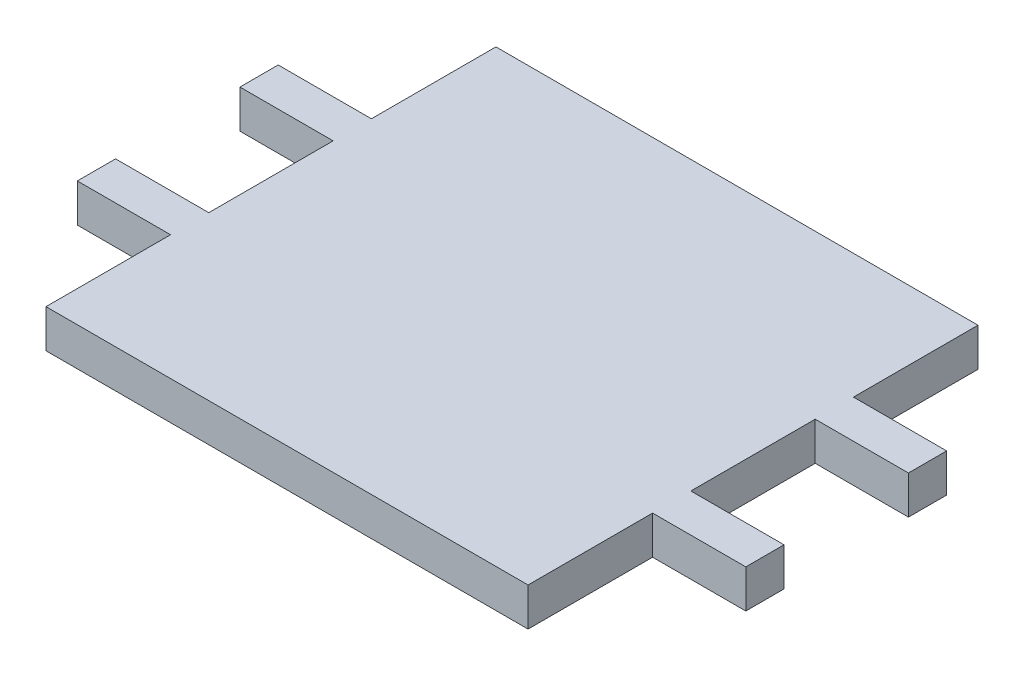
SolidWorks part; units mm, degrees
ref_plane "Front Plane" through (0, 0, 0) normal (0, 0, 1) x (1, 0, 0)
ref_plane "Top Plane" through (0, 0, 0) normal (0, 1, 0) x (1, 0, 0)
ref_plane "Right Plane" through (0, 0, 0) normal (1, 0, 0) x (0, 0, -1)
sketch "Sketch1" plane through (0, 0, 0) normal (0, 1, 0) x (1, 0, 0)
  line L0 (0, 35.56) -> (0, -35.56) construction
  line L1 (-38.1, 35.56) -> (38.1, 35.56)
  line L2 (-38.1, 35.56) -> (-38.1, -35.56)
  line L3 (-38.1, -35.56) -> (38.1, -35.56)
  line L4 (38.1, 35.56) -> (38.1, -35.56)
  line L5 (-38.1, 0) -> (38.1, 0) construction
  line L6 (-52.832, 9.8298) -> (-52.832, -9.8298) construction
  line L7 (-52.832, 15.875) -> (-38.1, 15.875)
  line L8 (-52.832, 15.875) -> (-52.832, 9.8298)
  line L9 (-52.832, 9.8298) -> (-38.1, 9.8298)
  line L10 (-38.1, 15.875) -> (-38.1, 9.8298)
  line L11 (-52.832, -9.8298) -> (-38.1, -9.8298)
  line L12 (-52.832, -9.8298) -> (-52.832, -15.875)
  line L13 (-52.832, -15.875) -> (-38.1, -15.875)
  line L14 (-38.1, -9.8298) -> (-38.1, -15.875)
  line L15 (52.832, -15.875) -> (38.1, -15.875)
  line L16 (38.1, -9.8298) -> (38.1, -15.875)
  line L17 (52.832, -9.8298) -> (38.1, -9.8298)
  line L18 (52.832, -9.8298) -> (52.832, -15.875)
  line L19 (52.832, 9.8298) -> (38.1, 9.8298)
  line L20 (38.1, 15.875) -> (38.1, 9.8298)
  line L21 (52.832, 15.875) -> (38.1, 15.875)
  line L22 (52.832, 15.875) -> (52.832, 9.8298)
  point P4 (0, 35.56)
  point P6 (-38.1, 0)
  point P19 (-52.832, 0)
  dimension "D1" = 76.2
  dimension "D2" = 71.12
  dimension "D3" = 14.732
  dimension "D4" = 6.0452
  dimension "D5" = 14.732
  dimension "D6" = 6.0452
  dimension "D7" = 31.75
extrude "Boss-Extrude1" add sketch "Sketch1" along normal blind 6.0452 contours L4 L1 L2 L3 | L12 L13 L2 L11 | L8 L9 L2 L7 | L22 L21 L4 L19 | L18 L17 L4 L15
